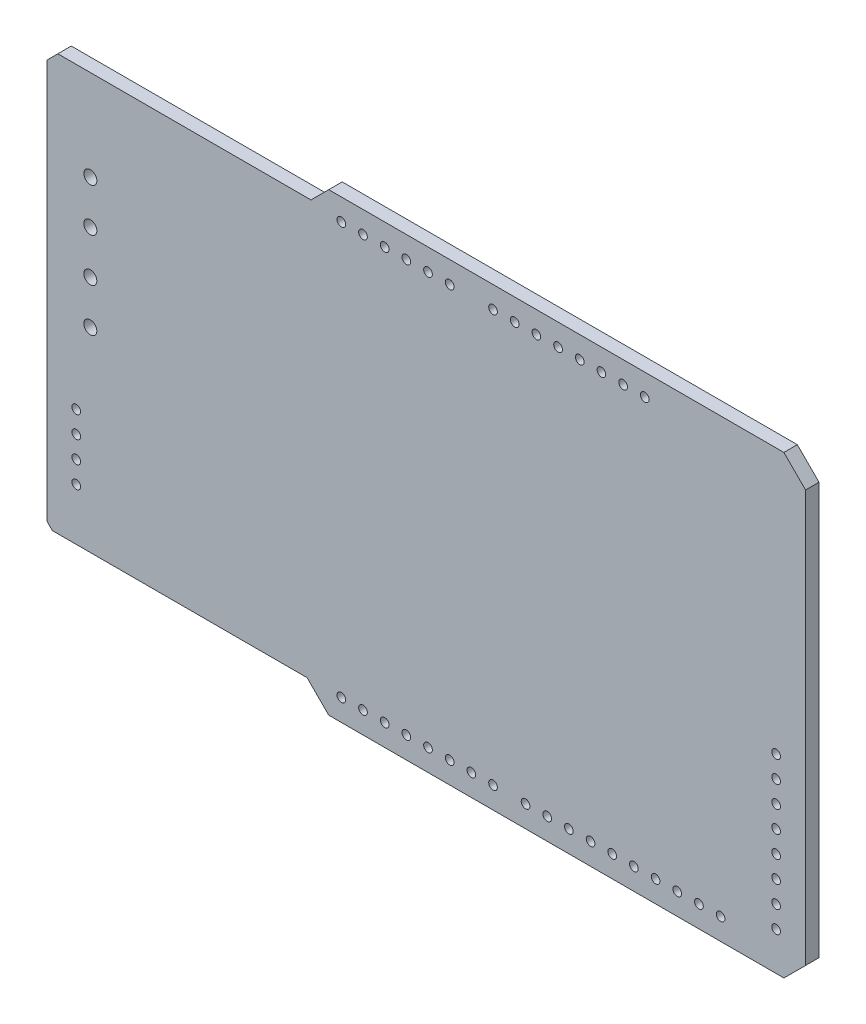
SolidWorks part; units mm, degrees
ref_plane "Front Plane" through (0, 0, 0) normal (0, 0, 1) x (1, 0, 0)
ref_plane "Top Plane" through (0, 0, 0) normal (0, 1, 0) x (1, 0, 0)
ref_plane "Right Plane" through (0, 0, 0) normal (1, 0, 0) x (0, 0, -1)
sketch "Sketch1" plane through (0, 0, 0) normal (0, 0, 1) x (1, 0, 0)
  line L0 (0, 49.9872) -> (1.27, 51.2572)
  line L1 (0, 0) -> (88.9, 0) construction
  line L2 (0, 0) -> (0, 53.34) construction
  line L3 (0, 53.34) -> (88.9, 53.34) construction
  line L4 (88.9, 0) -> (88.9, 53.34) construction
  line L5 (1.27, 51.2572) -> (30.9372, 51.2572)
  line L6 (30.9372, 51.2572) -> (33.02, 53.34)
  line L7 (33.02, 53.34) -> (86.36, 53.34)
  line L8 (86.36, 53.34) -> (88.9, 50.8)
  line L9 (88.9, 50.8) -> (88.9, 2.54)
  line L10 (88.9, 2.54) -> (86.36, 0)
  line L11 (86.36, 0) -> (33.02, 0)
  line L12 (33.02, 0) -> (30.48, 2.54)
  line L13 (30.48, 2.54) -> (0.635, 2.54)
  line L14 (0.635, 2.54) -> (0, 3.175)
  line L15 (0, 3.175) -> (0, 49.9872)
  dimension "D1" = 53.34
  dimension "D2" = 88.9
  dimension "D3" = 45
  dimension "D4" = 45
  dimension "D5" = 45
  dimension "D6" = 45
  dimension "D7" = 2.54
  dimension "D8" = 33.02
  dimension "D9" = 1.27
  dimension "D10" = 51.2572
  dimension "D11" = 1.27
extrude "Boss-Extrude1" add sketch "Sketch1" along normal blind 1.5748
sketch "Sketch2" plane through (0, 0, 1.5748) normal (0, 0, 1) x (1, 0, 0)
  line L0 (3.429, 8.636) -> (3.429, 16.256) construction
  line L1 (0, 49.9872) -> (0, 3.175) construction
  line L2 (0.635, 2.54) -> (30.48, 2.54) construction
  line L3 (5.08, 25.4) -> (5.08, 40.64) construction
  line L4 (33.02, 0) -> (86.36, 0) construction
  line L5 (85.4456, 4.4958) -> (85.4456, 22.2758) construction
  line L6 (34.4932, 2.54) -> (52.2732, 2.54) construction
  line L7 (56.0832, 2.54) -> (78.9432, 2.54) construction
  line L8 (34.4932, 50.8) -> (47.1932, 50.8) construction
  line L9 (52.2732, 50.8) -> (70.0532, 50.8) construction
  circle A0 centre (3.429, 8.636) radius 0.508
  circle A1 centre (3.429, 11.176) radius 0.508
  circle A2 centre (3.429, 13.716) radius 0.508
  circle A3 centre (3.429, 16.256) radius 0.508
  circle A4 centre (5.08, 25.4) radius 0.762
  circle A5 centre (5.08, 30.48) radius 0.762
  circle A6 centre (5.08, 35.56) radius 0.762
  circle A7 centre (5.08, 40.64) radius 0.762
  circle A8 centre (85.4456, 4.4958) radius 0.508
  circle A9 centre (85.4456, 7.0358) radius 0.508
  circle A10 centre (85.4456, 9.5758) radius 0.508
  circle A11 centre (85.4456, 12.1158) radius 0.508
  circle A12 centre (85.4456, 14.6558) radius 0.508
  circle A13 centre (85.4456, 17.1958) radius 0.508
  circle A14 centre (85.4456, 19.7358) radius 0.508
  circle A15 centre (85.4456, 22.2758) radius 0.508
  circle A16 centre (34.4932, 50.8) radius 0.508
  circle A17 centre (37.0332, 50.8) radius 0.508
  circle A18 centre (39.5732, 50.8) radius 0.508
  circle A19 centre (42.1132, 50.8) radius 0.508
  circle A20 centre (44.6532, 50.8) radius 0.508
  circle A21 centre (47.1932, 50.8) radius 0.508
  circle A22 centre (49.7332, 50.8) radius 0.508 [skipped]
  circle A23 centre (52.2732, 50.8) radius 0.508
  circle A24 centre (54.8132, 50.8) radius 0.508
  circle A25 centre (57.3532, 50.8) radius 0.508
  circle A26 centre (59.8932, 50.8) radius 0.508
  circle A27 centre (62.4332, 50.8) radius 0.508
  circle A28 centre (64.9732, 50.8) radius 0.508
  circle A29 centre (67.5132, 50.8) radius 0.508
  circle A30 centre (70.0532, 50.8) radius 0.508
  circle A31 centre (34.4932, 2.54) radius 0.508
  circle A32 centre (37.0332, 2.54) radius 0.508
  circle A33 centre (39.5732, 2.54) radius 0.508
  circle A34 centre (42.1132, 2.54) radius 0.508
  circle A35 centre (44.6532, 2.54) radius 0.508
  circle A36 centre (47.1932, 2.54) radius 0.508
  circle A37 centre (49.7332, 2.54) radius 0.508
  circle A38 centre (52.2732, 2.54) radius 0.508
  circle A39 centre (56.0832, 2.54) radius 0.508
  circle A40 centre (58.6232, 2.54) radius 0.508
  circle A41 centre (61.1632, 2.54) radius 0.508
  circle A42 centre (63.7032, 2.54) radius 0.508
  circle A43 centre (66.2432, 2.54) radius 0.508
  circle A44 centre (68.7832, 2.54) radius 0.508
  circle A45 centre (71.3232, 2.54) radius 0.508
  circle A46 centre (73.8632, 2.54) radius 0.508
  circle A47 centre (76.4032, 2.54) radius 0.508
  circle A48 centre (78.9432, 2.54) radius 0.508
  point P46 (59.69, 0)
  dimension "D4" = 1.016
  dimension "D10" = 1.524
  dimension "D15" = 1.016
  dimension "D26" = 1.016
  dimension "D28" = 1.016
  dimension "D30" = 1.016
  dimension "D1" = 7.62
  dimension "D2" = 3.429
  dimension "D3" = 13.716
  dimension "D5" = 2.54
  dimension "D6" = 2.54
  dimension "D7" = 15.24
  dimension "D8" = 5.08
  dimension "D9" = 25.4
  dimension "D12" = 17.78
  dimension "D13" = 85.4456
  dimension "D14" = 4.4958
  dimension "D17" = 17.78
  dimension "D18" = 22.86
  dimension "D19" = 12.7
  dimension "D20" = 17.78
  dimension "D21" = 2.54
  dimension "D22" = 50.8
  dimension "D23" = 34.4932
  dimension "D24" = 3.81
  dimension "D25" = 5.08
  dimension "D11" = 4
  dimension "D16" = 8
  dimension "D27" = 15
  dimension "D29" = 8
  dimension "D31" = 10
extrude "Cut-Extrude1" cut sketch "Sketch2" against normal through all
